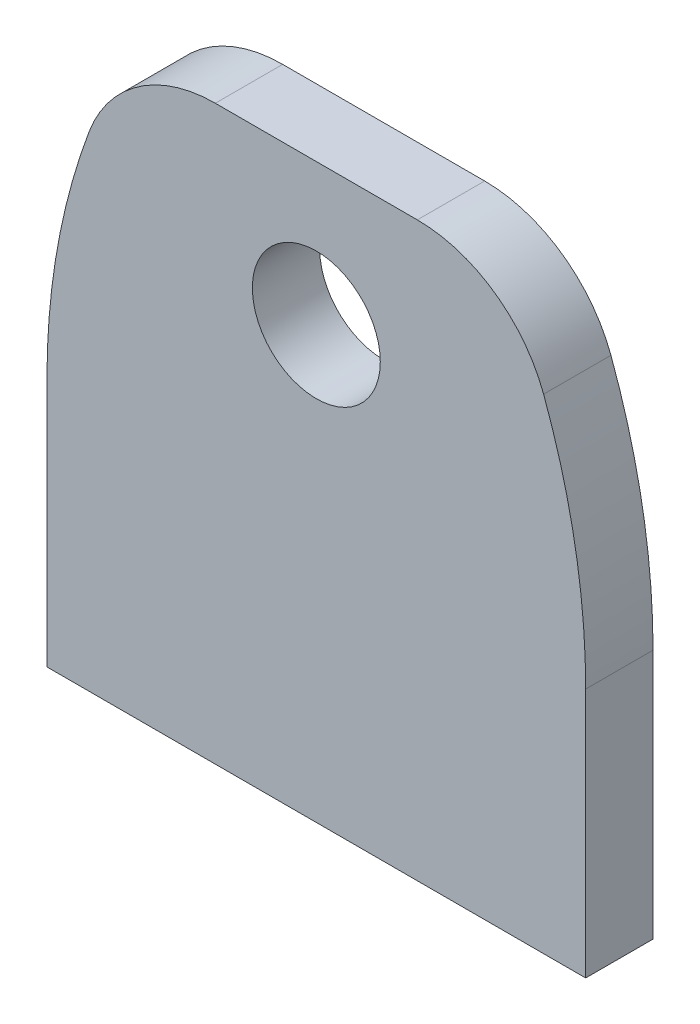
SolidWorks part; units mm, degrees
ref_plane "Plan de face" through (0, 0, 0) normal (0, 0, 1) x (1, 0, 0)
ref_plane "Plan de dessus" through (0, 0, 0) normal (0, 1, 0) x (1, 0, 0)
ref_plane "Plan de droite" through (0, 0, 0) normal (1, 0, 0) x (0, 0, -1)
sketch "Esquisse1" plane through (0, 0, 0) normal (0, 0, 1) x (1, 0, 0)
  line L0 (0, 0) -> (0, 37.1612)
  line L1 (25, 85) -> (55, 85)
  line L3 (80, 0) -> (0, 0)
  line L4 (40, 0) -> (40, 136.4494) construction
  line L5 (80, 0) -> (80, 37.1612)
  arc A0 (0, 37.1612) -> (6.25, 71.9597) centre (100, 37.1612) cw
  arc A1 (6.25, 71.9597) -> (25, 85) centre (25, 65) cw
  arc A4 (73.75, 71.9597) -> (55, 85) centre (55, 65) ccw
  arc A5 (80, 37.1612) -> (73.75, 71.9597) centre (-20, 37.1612) ccw
  point P11 (40, 85)
  dimension "D1" = 85
  dimension "D3" = 100
  dimension "D4" = 20
  dimension "D2" = 25
  dimension "D5" = 80
extrude "Boss.-Extru.1" add sketch "Esquisse1" along normal blind 10
hole_wizard "Dégagement M41" positions "Esquisse2" profile "Esquisse3" hole size "M4" standard "ISO" end condition up to next
sketch "Esquisse2" plane through (0, 0, 10) normal (0, 0, 1) x (1, 0, 0)
  line L0 (0, 0) -> (80, 0) construction
  point P0 (40, 64)
  dimension "D1" = 64
sketch "Esquisse3" plane through (40, 64, 10) normal (1, 0, 0) x (0, -1, 0)
  line L0 (0, 0) -> (0, 10)
  line L1 (0, 10) -> (9.5, 10)
  line L2 (9.5, 10) -> (9.5, 0)
  line L5 (9.5, 0) -> (0, 0)
  line L11 (0, -6.35) -> (0, 107.95) construction
  dimension "Diamètre du perçage jusqu'au prochain" = 19
  dimension "Profondeur du perçage jusqu'au prochain" = 10
